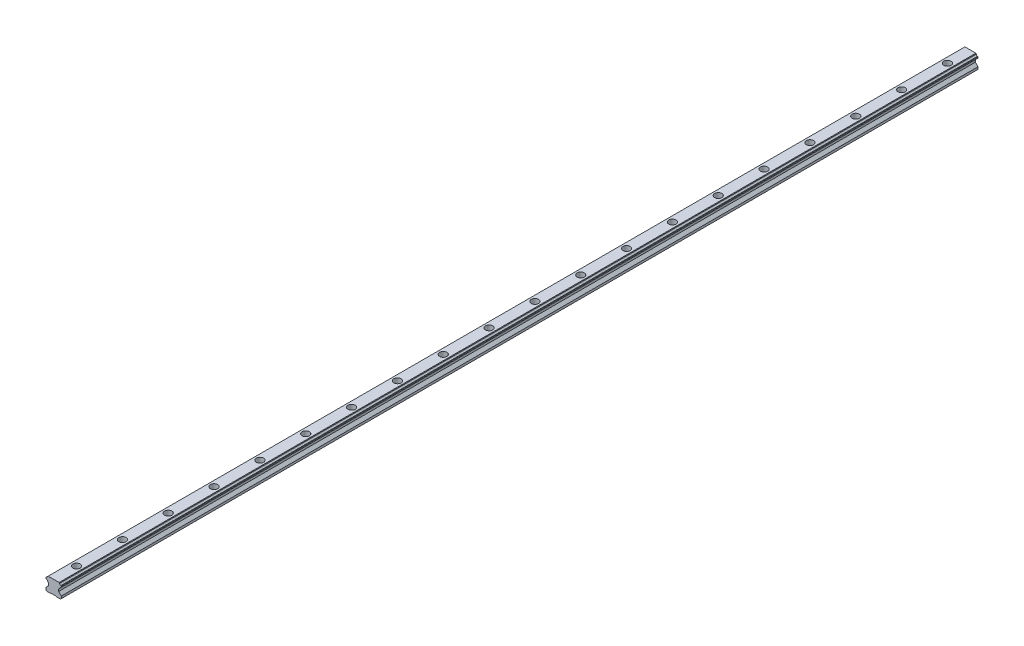
SolidWorks part; units mm, degrees
material "Plain Carbon Steel"
ref_plane "Front Plane" through (0, 0, 0) normal (0, 0, 1) x (1, 0, 0)
ref_plane "Top Plane" through (0, 0, 0) normal (0, 1, 0) x (1, 0, 0)
ref_plane "Right Plane" through (0, 0, 0) normal (1, 0, 0) x (0, 0, -1)
sketch "Sketch1" plane through (0, 0, 0) normal (0, 0, 1) x (1, 0, 0)
  line L0 (-10, -10.4945) -> (-10, -13.4946)
  line L1 (-10, -13.4946) -> (-9, -14.4946)
  line L2 (-9, -14.4946) -> (-3, -14.4946)
  line L3 (-3, -14.4946) -> (-2.5, -13.9946)
  line L4 (-2.5, -13.9946) -> (2.5, -13.9946)
  line L5 (6.55, -7.0447) -> (10, -10.4945)
  line L6 (6.55, -4.1154) -> (6.55, -7.0447)
  line L7 (7.7679, -2.8995) -> (6.55, -4.1154)
  line L8 (10, -0.6654) -> (9.4727, -1.1802)
  line L9 (10, 0.6654) -> (10, -0.6654)
  line L10 (9.4727, 1.1928) -> (10, 0.6654)
  line L11 (7.16, 3.5054) -> (7.7679, 2.8975)
  line L12 (3, -14.4946) -> (2.5, -13.9946)
  line L13 (9, -14.4946) -> (3, -14.4946)
  line L14 (10, -13.4946) -> (9, -14.4946)
  line L15 (10, -10.4945) -> (10, -13.4946)
  line L16 (7.16, 3.5054) -> (-7.16, 3.5054)
  line L17 (-7.16, 3.5054) -> (-7.7679, 2.8975)
  line L18 (-9.4727, 1.1928) -> (-10, 0.6654)
  line L19 (-10, 0.6654) -> (-10, -0.6654)
  line L20 (-10, -0.6654) -> (-9.4727, -1.1802)
  line L21 (-7.7679, -2.8995) -> (-6.55, -4.1154)
  line L22 (-6.55, -4.1154) -> (-6.55, -7.0447)
  line L23 (-6.55, -7.0447) -> (-10, -10.4945)
  line L24 (0, -14.4946) -> (0, -13.9946) construction
  line L25 (0, -13.9946) -> (0, 3.5054) construction
  line L26 (55, 0) -> (-55, 0) construction
  arc A0 (9.4727, -1.1802) -> (7.7679, -2.8995) centre (9.8039, -3.2134) ccw
  arc A1 (7.7679, 2.8975) -> (9.4727, 1.1928) centre (9.8015, 3.2263) ccw
  arc A2 (-7.7679, 2.8975) -> (-9.4727, 1.1928) centre (-9.8015, 3.2263) cw
  arc A3 (-9.4727, -1.1802) -> (-7.7679, -2.8995) centre (-9.8039, -3.2134) cw
  point P38 (10, 0)
  dimension "D17" = 2.06
  dimension "D1" = 20
  dimension "D2" = 1
  dimension "D3" = 1
  dimension "D4" = 0.5
  dimension "D5" = 0.5
  dimension "D6" = 6
  dimension "D7" = 18
  dimension "D8" = 4.0001
  dimension "D9" = 10.55
  dimension "D10" = 13.1001
  dimension "D11" = 15.5359
  dimension "D12" = 0.6079
  dimension "D13" = 0.6079
  dimension "D14" = 17.5
  dimension "D15" = 0.5273
  dimension "D16" = 0.5273
  dimension "D18" = 1.2159
  dimension "D19" = 0.5148
  dimension "D20" = 6.4049
  dimension "D21" = 2.84
  dimension "D22" = 4.1708
extrude "Boss-Extrude1" add sketch "Sketch1" against normal mid plane 1200
sketch "Sketch2" plane through (0, 0, 0) normal (1, 0, 0) x (0, 0, -1)
  line L0 (-570, 3.5054) -> (-570, -14.4946)
  line L1 (600, 3.5054) -> (-600, 3.5054) construction
  line L2 (600, -14.4946) -> (-600, -14.4946) construction
  line L3 (-570, -14.4946) -> (-573, -14.4946)
  line L4 (-573, -14.4946) -> (-573, -4.9946)
  line L5 (-573, -4.9946) -> (-574.75, -4.9946)
  line L6 (-574.75, -4.9946) -> (-574.75, 3.5054)
  line L7 (-574.75, 3.5054) -> (-570, 3.5054)
  line L8 (-600, -7.0447) -> (-600, -4.1154) construction
  point P12 (-600, -5.58)
  dimension "D1" = 3
  dimension "D2" = 4.75
  dimension "D3" = 8.5
  dimension "D4" = 30
revolve "Cut-Revolve1" cut sketch "Sketch2" angle 360 about L0
pattern_linear "LPattern1" count 20 spacing 60 along (0, 0, -1) of "Cut-Revolve1"
